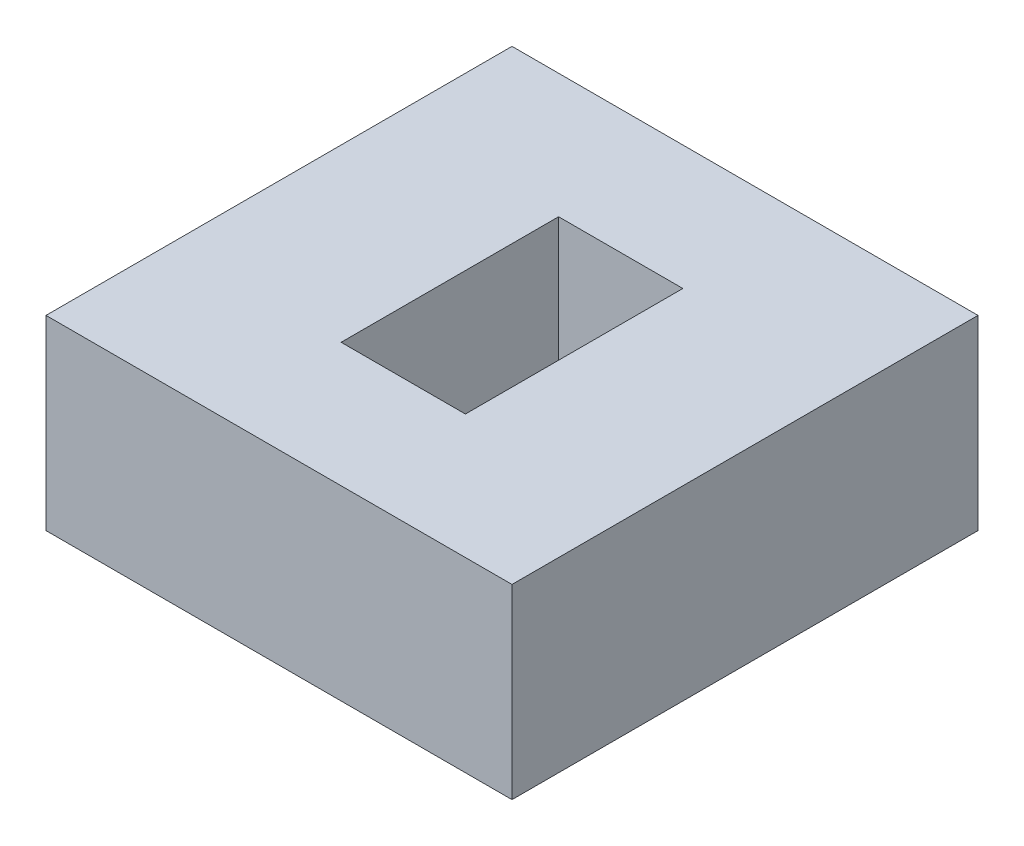
SolidWorks part; units mm, degrees
ref_plane "Front Plane" through (0, 0, 0) normal (0, 0, 1) x (1, 0, 0)
ref_plane "Top Plane" through (0, 0, 0) normal (0, 1, 0) x (1, 0, 0)
ref_plane "Right Plane" through (0, 0, 0) normal (1, 0, 0) x (0, 0, -1)
sketch "Sketch1" plane through (0, 0, 0) normal (0, 1, 0) x (1, 0, 0)
  line L0 (0, 0) -> (0, 75)
  line L1 (0, 75) -> (75, 75)
  line L2 (75, 75) -> (75, 0)
  line L3 (75, 0) -> (0, 0)
  dimension "D1" = 75
  dimension "D2" = 75
extrude "Boss-Extrude1" add sketch "Sketch1" along normal blind 30
sketch "Sketch2" plane through (0, 30, 0) normal (0, 1, 0) x (1, 0, 0)
  line L0 (27.5, 20) -> (27.5, 55)
  line L1 (27.5, 55) -> (47.5, 55)
  line L2 (47.5, 55) -> (47.5, 20)
  line L3 (47.5, 20) -> (27.5, 20)
  dimension "D1" = 20
  dimension "D2" = 35
  dimension "D3" = 27.5
  dimension "D4" = 20
extrude "Cut-Extrude1" cut sketch "Sketch2" against normal through all
